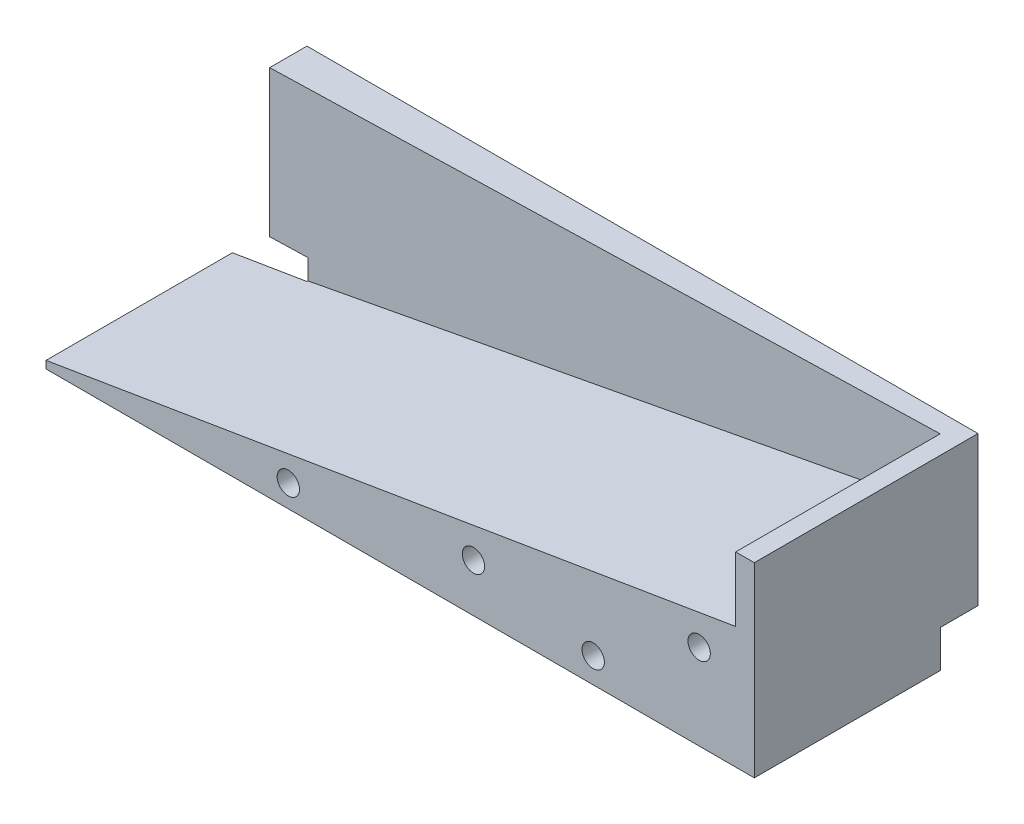
SolidWorks part; units mm, degrees
ref_plane "Plan de face" through (0, 0, 0) normal (0, 0, 1) x (1, 0, 0)
ref_plane "Plan de dessus" through (0, 0, 0) normal (0, 1, 0) x (1, 0, 0)
ref_plane "Plan de droite" through (0, 0, 0) normal (1, 0, 0) x (0, 0, -1)
sketch "Esquisse1" plane through (0, 0, 0) normal (0, 0, 1) x (1, 0, 0)
  line L0 (-105.796, 0) -> (84.204, 0)
  line L1 (84.204, 0) -> (84.204, 33.5021)
  line L2 (84.204, 25.3929) -> (-68.9493, 0) construction
  line L3 (-105.796, 0) -> (-105.796, 2)
  line L4 (-105.796, 2) -> (84.204, 33.5021)
  line L5 (40.9815, 6.7762) -> (8.8615, 12.9011) construction
  line L6 (69.406, 22.9394) -> (40.9815, 6.7762) construction
  circle A0 centre (69.406, 22.9394) radius 3
  circle A1 centre (40.9815, 6.7762) radius 3
  circle A2 centre (-40.796, 6) radius 3
  circle A3 centre (8.8615, 12.9011) radius 3
  dimension "D3" = 6
  dimension "D6" = 6
  dimension "D8" = 6
  dimension "D11" = 6
  dimension "D1" = 190
  dimension "D2" = 2
  dimension "D4" = 15
  dimension "D7" = 8
  dimension "D9" = 6
  dimension "D10" = 65
extrude "Boss.-Extru.1" add sketch "Esquisse1" along normal blind 200
sketch "Esquisse4" plane through (84.204, 0, 0) normal (1, 0, 0) x (0, 0, -1)
  line L1 (-200, 0) -> (-205, 0)
  line L2 (-200, 0) -> (-200, 50)
  line L3 (-200, 50) -> (-205, 50)
  line L4 (-205, 0) -> (-205, 50)
  line L5 (0, 0) -> (5, 0)
  line L6 (0, 0) -> (0, 50)
  line L7 (0, 50) -> (5, 50)
  line L8 (5, 0) -> (5, 50)
  dimension "D1" = 50
  dimension "D2" = 5
  dimension "D3" = 5
  dimension "D4" = 50
extrude "Boss.-Extru.4" add sketch "Esquisse4" against normal blind 180
sketch "Esquisse8" plane through (0, 50, 0) normal (0, 1, 0) x (1, 0, 0)
  line L0 (84.204, 0) -> (-95.796, 0)
  line L1 (-95.796, 0) -> (-95.796, -5)
  line L2 (-95.796, -5) -> (84.204, 0)
  dimension "D1" = 5
extrude "Boss.-Extru.7" add sketch "Esquisse8" against normal up to surface (50 mm away)
ref_plane "Plan2" through (-5.796, 0, 0) normal (1, 0, 0) x (0, 0, -1)
sketch "Esquisse6" plane through (0, 0, -5) normal (0, 0, -1) x (-1, 0, 0)
  line L1 (105.796, 0) -> (85.796, 0)
  line L2 (105.796, 0) -> (105.796, 10.7198)
  line L3 (105.796, 10.7198) -> (85.796, 10.7198)
  line L4 (85.796, 0) -> (85.796, 10.7198)
  line L5 (95.796, 0) -> (95.796, 50) construction
  dimension "D1" = 10
extrude "Enlèv. mat.-Extru.2" cut sketch "Esquisse6" against normal blind 10
ref_plane "Plan3" through (0, 0, 100) normal (0, 0, -1) x (-1, 0, 0)
sketch "Esquisse5" plane through (84.204, 0, 0) normal (1, 0, 0) x (0, 0, -1)
  line L1 (-205, 0) -> (-195, 0)
  line L2 (-205, 0) -> (-205, 10)
  line L3 (-205, 10) -> (-195, 10)
  line L4 (-195, 0) -> (-195, 10)
  line L5 (5, 0) -> (-5, 0)
  line L6 (5, 0) -> (5, 10)
  line L7 (5, 10) -> (-5, 10)
  line L8 (-5, 0) -> (-5, 10)
  dimension "D1" = 10
  dimension "D2" = 10
  dimension "D3" = 10
  dimension "D4" = 10
extrude "Enlèv. mat.-Extru.1" cut sketch "Esquisse5" against normal blind 10
sketch "Esquisse14" plane through (0, 0, -5) normal (0, 0, -1) x (-1, 0, 0)
  circle A0 centre (-69.406, 22.9394) radius 5
  circle A1 centre (-40.9815, 6.7762) radius 5
  circle A2 centre (-8.8615, 12.9011) radius 5
  circle A3 centre (40.796, 6) radius 5
  dimension "D1" = 10
  dimension "D2" = 10
  dimension "D3" = 10
  dimension "D4" = 10
extrude "Enlèv. mat.-Extru.4" cut sketch "Esquisse14" against normal blind 15
mirror "Symétrie3" about plane through (0, 0, 100) normal (0, 0, -1) of "Enlèv. mat.-Extru.4", "Boss.-Extru.7", "Enlèv. mat.-Extru.2"
sketch "Esquisse15" plane through (0, 0, -5) normal (0, 0, -1) x (-1, 0, 0)
  line L0 (-84.204, 33.5021) -> (-79.204, 32.6731)
  line L1 (-84.204, 33.5021) -> (85.796, 5.316) construction
  line L2 (-79.204, 32.6731) -> (-79.204, 50)
  line L3 (95.796, 50) -> (-84.204, 50) construction
  line L4 (-79.204, 50) -> (-84.204, 50)
  line L5 (-84.204, 50) -> (-84.204, 33.5021)
  dimension "D1" = 5
extrude "Boss.-Extru.8" add sketch "Esquisse15" against normal up to surface (204.8611 mm away)
sketch "Esquisse16" plane through (0, 50, 0) normal (0, 1, 0) x (1, 0, 0)
  line L0 (-105.796, -195) -> (-105.796, -5) construction
  line L1 (84.204, -205) -> (-105.796, -205)
  line L2 (84.204, -205) -> (84.204, -55)
  line L3 (84.204, -55) -> (-105.796, -55)
  line L4 (-105.796, -205) -> (-105.796, -55)
  line L5 (-95.796, 5) -> (84.204, 5) construction
  dimension "D1" = 60
extrude "Enlèv. mat.-Extru.5" cut sketch "Esquisse16" against normal up to surface (50 mm away) up to face at (9.5373, 0, 119.9815)
